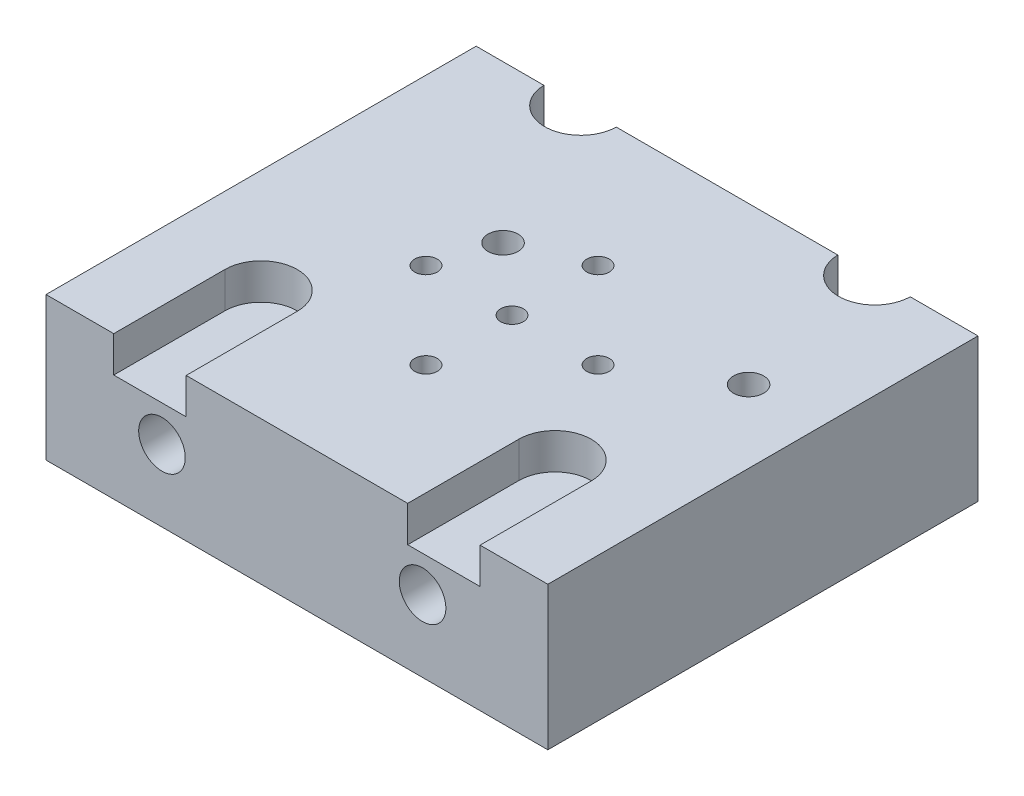
SolidWorks part; units mm, degrees
ref_plane "Front Plane" through (0, 0, 0) normal (0, 0, 1) x (1, 0, 0)
ref_plane "Top Plane" through (0, 0, 0) normal (0, 1, 0) x (1, 0, 0)
ref_plane "Right Plane" through (0, 0, 0) normal (1, 0, 0) x (0, 0, -1)
sketch "Sketch3" plane through (0, 0, 0) normal (0, 1, 0) x (1, 0, 0)
  line L1 (0, 0) -> (70, 0)
  line L2 (0, 0) -> (0, -60)
  line L3 (0, -60) -> (70, -60)
  line L4 (70, 0) -> (70, -60)
  dimension "D1" = 70
  dimension "D2" = 60
extrude "Boss-Extrude3" add sketch "Sketch3" along normal blind 20
sketch "Sketch4" plane through (0, 20, 0) normal (0, 1, 0) x (1, 0, 0)
  line L0 (35, 0) -> (35, -60) construction
  line L1 (70, 0) -> (0, 0) construction
  line L2 (0, -60) -> (70, -60) construction
  line L3 (0, -30) -> (70, -30) construction
  line L4 (0, 0) -> (0, -60) construction
  line L5 (70, -60) -> (70, 0) construction
  line L6 (21.425, -30) -> (21.425, 0) construction
  line L7 (0, 0) -> (70, 0) construction
  line L8 (24.575, -30) -> (24.575, 0) construction
  line L9 (45.425, -30) -> (45.425, 0) construction
  line L10 (48.575, -30) -> (48.575, 0) construction
  circle A0 centre (35, -30) radius 1.575
  circle A1 centre (35, -18) radius 1.575
  circle A2 centre (47, -30) radius 1.575
  circle A3 centre (35, -42) radius 1.575
  circle A4 centre (23, -30) radius 1.575
  dimension "D1" = 3.15
  dimension "D2" = 12
  dimension "D3" = 12
  dimension "D4" = 12
  dimension "D5" = 12
extrude "Cut-Extrude1" cut sketch "Sketch4" against normal through all
sketch "Sketch6" plane through (0, 0, 0) normal (0, -1, 0) x (1, 0, 0)
  line L0 (70, 30) -> (0, 30) construction
  line L1 (51.75, 21.875) -> (33.75, 21.875) construction
  line L2 (68, 21.875) -> (70, 21.875) construction
  line L3 (70, 60) -> (70, 0) construction
  line L4 (0, 0) -> (0, 60) construction
  line L5 (25.625, 21.875) -> (25.625, 0) construction
  line L6 (70, 0) -> (0, 0) construction
  line L7 (59.875, 21.875) -> (59.875, 0) construction
  line L8 (33.75, 21.875) -> (33.75, 0) construction
  line L9 (51.75, 21.875) -> (51.75, 0) construction
  line L10 (17.5, 21.875) -> (17.5, 0) construction
  line L11 (68, 21.875) -> (68, 0) construction
  line L12 (57.775, 21.875) -> (57.775, 0) construction
  line L13 (61.975, 21.875) -> (61.975, 0) construction
  line L14 (27.725, 21.875) -> (27.725, 0) construction
  line L15 (23.525, 21.875) -> (23.525, 0) construction
  line L17 (34.9353, 16.4263) -> (34.9353, 0) construction
  circle A2 centre (59.875, 21.875) radius 8.125 construction
  circle A3 centre (25.625, 21.875) radius 8.125 construction
  circle A4 centre (59.875, 21.875) radius 2.1
  circle A5 centre (25.625, 21.875) radius 2.1
  circle A6 centre (35, 18) radius 1.575 construction
  dimension "D1" = 16.25
  dimension "D2" = 18
  dimension "D3" = 4.2
  dimension "D4" = 2
extrude "Cut-Extrude2" cut sketch "Sketch6" against normal through all contours A4 | A5
sketch "Sketch9" plane through (0, 0, 0) normal (0, 0, -1) x (-1, 0, 0)
  line L0 (-25.625, 0) -> (-25.625, 20) construction
  line L1 (-70, 20) -> (0, 20) construction
  line L2 (-59.875, 0) -> (-59.875, 20) construction
  line L3 (-68, 0) -> (-51.75, 0) construction
  line L4 (-17.5, 0) -> (-17.5, 20) construction
  line L5 (-33.75, 0) -> (-33.75, 20) construction
  line L6 (-51.75, 0) -> (-51.75, 20) construction
  line L7 (-68, 0) -> (-68, 20) construction
  line L8 (-57.775, 0) -> (-57.775, 20) construction
  line L9 (-61.975, 0) -> (-61.975, 20) construction
  line L10 (-27.725, 0) -> (-27.725, 20) construction
  line L11 (-23.525, 0) -> (-23.525, 20) construction
  line L12 (-57.775, 10) -> (-55.775, 10) construction
  line L13 (-52.525, 13.25) -> (-52.525, 20) construction
  line L14 (-12.925, 10) -> (0, 10) construction
  line L15 (-19.425, 10) -> (-21.425, 10) construction
  line L16 (-16.175, 20) -> (-16.175, 13.25) construction
  line L17 (0, 20) -> (0, 0) construction
  line L18 (-34.9353, 0) -> (-34.9353, 20) construction
  line L19 (-34.9353, 0) -> (-34.9353, 20) construction
  line L20 (-49.275, 10) -> (-34.9353, 10) construction
  line L21 (-21.425, 20) -> (-21.425, 0) construction
  line L22 (0, 0) -> (-70, 0) construction
  line L23 (-24.575, 20) -> (-24.575, 0) construction
  line L24 (-45.425, 20) -> (-45.425, 0) construction
  line L25 (-48.575, 20) -> (-48.575, 0) construction
  line L26 (0, 10) -> (0, 20) construction
  circle A0 centre (-52.525, 10) radius 3.25
  circle A1 centre (-16.175, 10) radius 3.25
  dimension "D1" = 6.5
  dimension "D2" = 2
  dimension "D3" = 2
  dimension "D4" = 10
extrude "Cut-Extrude3" cut sketch "Sketch9" against normal through all
sketch "Sketch11" plane through (0, 0, 0) normal (0, -1, 0) x (1, 0, 0)
  line L0 (70, 30) -> (0, 30) construction
  circle A0 centre (23, 30) radius 3
  circle A1 centre (35, 42) radius 3
  circle A2 centre (35, 30) radius 3
  circle A3 centre (35, 18) radius 3
  circle A4 centre (47, 30) radius 3
  circle M3 centre (35, 18) radius 1.575
  circle M4 centre (47, 30) radius 1.575
  circle M5 centre (35, 42) radius 1.575
  circle M6 centre (23, 30) radius 1.575
  circle M7 centre (35, 30) radius 1.575
  dimension "D1" = 6
extrude "Cut-Extrude4" cut sketch "Sketch11" against normal blind 3 contours A3 M3 | A2 M7 | A4 M4 | A0 M6 | A1 M5 | M5 | M6 | M7 | M4 | M3
chamfer "Chamfer1" distance 0.8 angle 45 2 edges at (49.275, 10, 0) (12.925, 10, 0)
sketch "Sketch12" plane through (0, 20, 0) normal (0, 1, 0) x (1, 0, 0)
  line L0 (35, -60.1049) -> (14.5, -60.1049) construction
  line L1 (35, 0.1049) -> (35, -60.1049) construction
  line L2 (14.5, -60.1049) -> (14.5, -44.5) construction
  line L3 (9.45, -60.1049) -> (9.45, -44.5)
  line L4 (19.55, -60.1049) -> (19.55, -44.5)
  line L5 (70, -30) -> (0, -30) construction
  line L6 (35, 0) -> (35, -60) construction
  line L7 (35, 0.1049) -> (14.5, 0.1049) construction
  line L8 (55.5, -60.1049) -> (55.5, -44.5) construction
  line L9 (60.55, -60.1049) -> (60.55, -44.5)
  line L10 (50.45, -60.1049) -> (50.45, -44.5)
  arc A0 (9.45, -60.1049) -> (19.55, -60.1049) centre (14.5, -60.1049) ccw
  arc A1 (19.55, -44.5) -> (9.45, -44.5) centre (14.5, -44.5) ccw
  circle A2 centre (14.5, 0.1049) radius 5.05
  arc A3 (60.55, -60.1049) -> (50.45, -60.1049) centre (55.5, -60.1049) cw
  arc A4 (50.45, -44.5) -> (60.55, -44.5) centre (55.5, -44.5) cw
  circle A5 centre (55.5, 0.1049) radius 5.05
  point P0 (14.5, -52.3025)
  point P19 (35, -30)
  point P23 (55.5, -52.3025)
  dimension "D4" = 5.05
  dimension "D5" = 10.1
  dimension "D1" = 20.5
extrude "Cut-Extrude5" cut sketch "Sketch12" against normal blind 5
